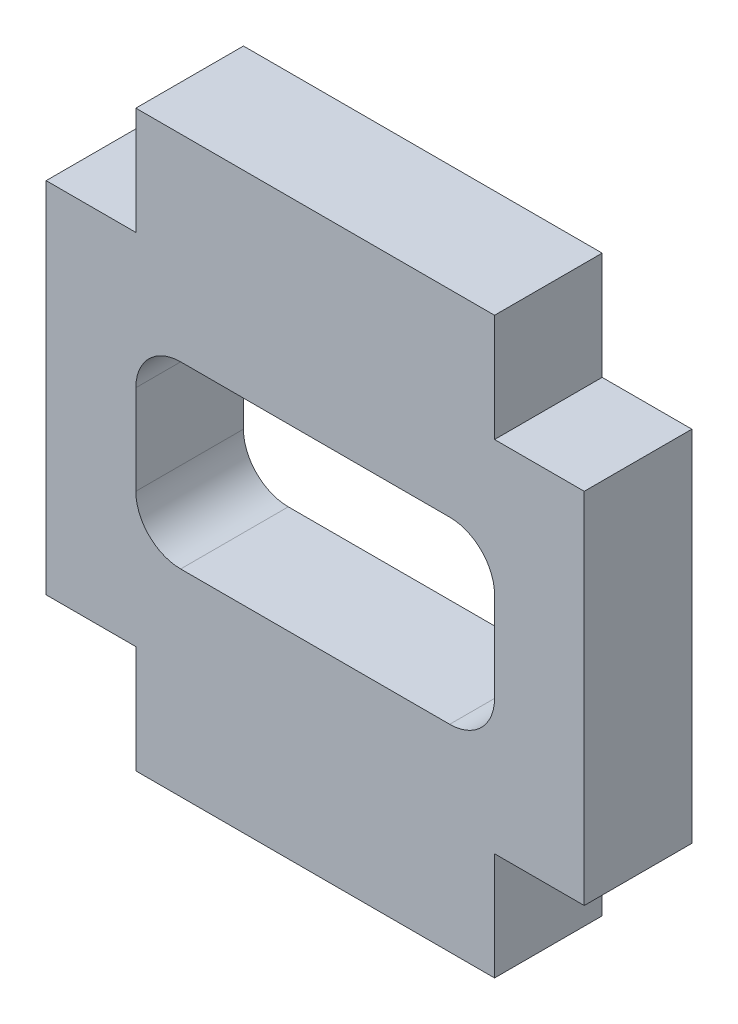
SolidWorks part; units mm, degrees
material "Acrílico (Impacto medio-alto)"
ref_plane "Alzado" through (0, 0, 0) normal (0, 0, 1) x (1, 0, 0)
ref_plane "Planta" through (0, 0, 0) normal (0, 1, 0) x (1, 0, 0)
ref_plane "Vista lateral" through (0, 0, 0) normal (1, 0, 0) x (0, 0, -1)
sketch "Croquis1" plane through (0, 0, 0) normal (0, 0, 1) x (1, 0, 0)
  line L0 (0, 0) -> (-7.6546, 0) construction
  line L1 (7.5, -8) -> (-7.5, -8)
  line L2 (7.5, -8) -> (7.5, 8)
  line L3 (7.5, 8) -> (-7.5, 8)
  line L4 (-7.5, -8) -> (-7.5, 8)
  line L5 (7.5, -8) -> (-7.5, 8) construction
  line L6 (7.5, 8) -> (-7.5, -8) construction
  line L7 (-10, 5) -> (-5, 5)
  line L8 (-10, 5) -> (-10, 11)
  line L9 (-10, 11) -> (-5, 11)
  line L10 (-5, 5) -> (-5, 11)
  line L11 (-10, 5) -> (-5, 11) construction
  line L12 (-10, 11) -> (-5, 5) construction
  line L13 (0, 0) -> (0, 14.1654) construction
  line L14 (10, 11) -> (5, 11)
  line L15 (5, 5) -> (5, 11)
  line L16 (10, 5) -> (5, 5)
  line L17 (10, 5) -> (10, 11)
  line L18 (-10, -11) -> (-5, -11)
  line L19 (-5, -5) -> (-5, -11)
  line L20 (-10, -5) -> (-5, -5)
  line L21 (-10, -5) -> (-10, -11)
  line L22 (10, -5) -> (10, -11)
  line L23 (10, -5) -> (5, -5)
  line L24 (5, -5) -> (5, -11)
  line L25 (10, -11) -> (5, -11)
  line L27 (3.75, -2.5) -> (-3.75, -2.5)
  line L28 (5, -1.25) -> (5, 1.25)
  line L29 (3.75, 2.5) -> (-3.75, 2.5)
  line L30 (-5, -1.25) -> (-5, 1.25)
  line L31 (5, -2.5) -> (-5, 2.5) construction
  line L32 (5, 2.5) -> (-5, -2.5) construction
  arc A0 (-3.75, -2.5) -> (-5, -1.25) centre (-3.75, -1.25) cw
  arc A1 (-3.75, 2.5) -> (-5, 1.25) centre (-3.75, 1.25) ccw
  arc A2 (5, 1.25) -> (3.75, 2.5) centre (3.75, 1.25) ccw
  arc A3 (5, -1.25) -> (3.75, -2.5) centre (3.75, -1.25) cw
  point P0 (0, 0)
  dimension "D7" = 1.25
  dimension "D1" = 16
  dimension "D2" = 15
  dimension "D3" = 6
  dimension "D4" = 5
  dimension "D5" = 5
  dimension "D6" = 10
extrude "Saliente-Extruir1" add sketch "Croquis1" along normal blind 3 contours L24 L23 L2 L16 L15 L3 L10 L7 L4 L20 L19 L1
